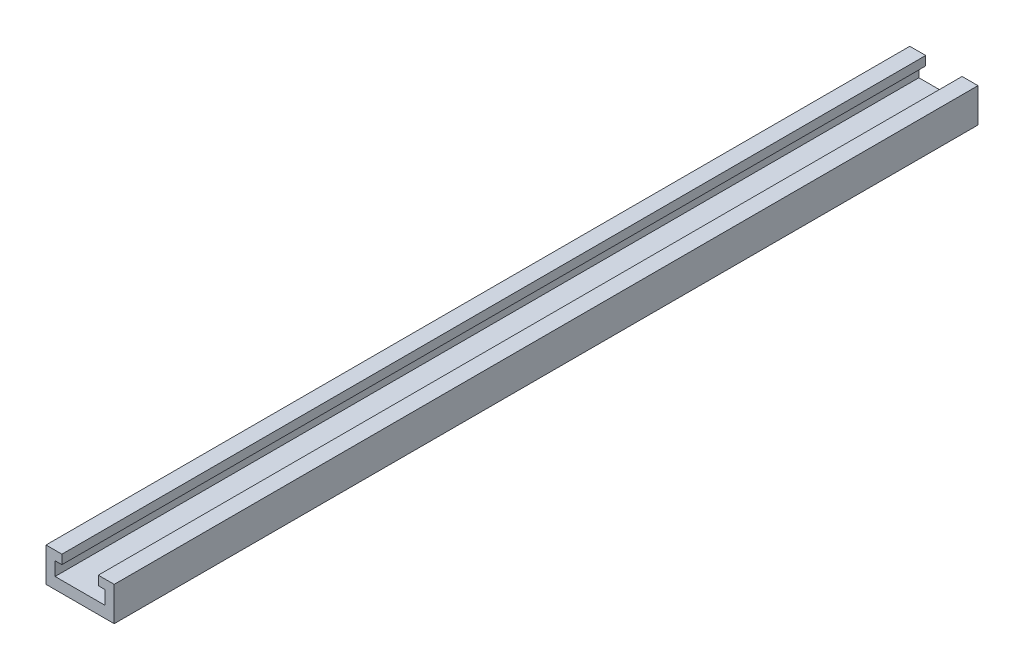
SolidWorks part; units mm, degrees
ref_plane "Front Plane" through (0, 0, 0) normal (0, 0, 1) x (1, 0, 0)
ref_plane "Top Plane" through (0, 0, 0) normal (0, 1, 0) x (1, 0, 0)
ref_plane "Right Plane" through (0, 0, 0) normal (1, 0, 0) x (0, 0, -1)
sketch "Sketch2" plane through (0, 0, 0) normal (0, 0, 1) x (1, 0, 0)
  line L0 (4.445, 9.525) -> (4.445, 6.985)
  line L1 (0, 0) -> (19.05, 0)
  line L2 (0, 0) -> (0, 9.525)
  line L3 (0, 9.525) -> (4.445, 9.525)
  line L4 (19.05, 0) -> (19.05, 9.525)
  line L5 (4.445, 6.985) -> (2.54, 6.985)
  line L6 (2.54, 6.985) -> (2.54, 3.175)
  line L7 (9.525, 0) -> (9.525, 3.175) construction
  line L8 (2.54, 3.175) -> (16.51, 3.175)
  line L9 (16.51, 6.985) -> (16.51, 3.175)
  line L10 (14.605, 6.985) -> (16.51, 6.985)
  line L11 (14.605, 9.525) -> (14.605, 6.985)
  line L12 (14.605, 9.525) -> (19.05, 9.525)
  point P13 (9.525, 3.175)
  dimension "D1" = 9.525
  dimension "D2" = 19.05
  dimension "D3" = 10.16
  dimension "D4" = 13.97
  dimension "D5" = 3.81
  dimension "D6" = 3.175
extrude "Boss-Extrude1" add sketch "Sketch2" along normal mid plane 241.3
